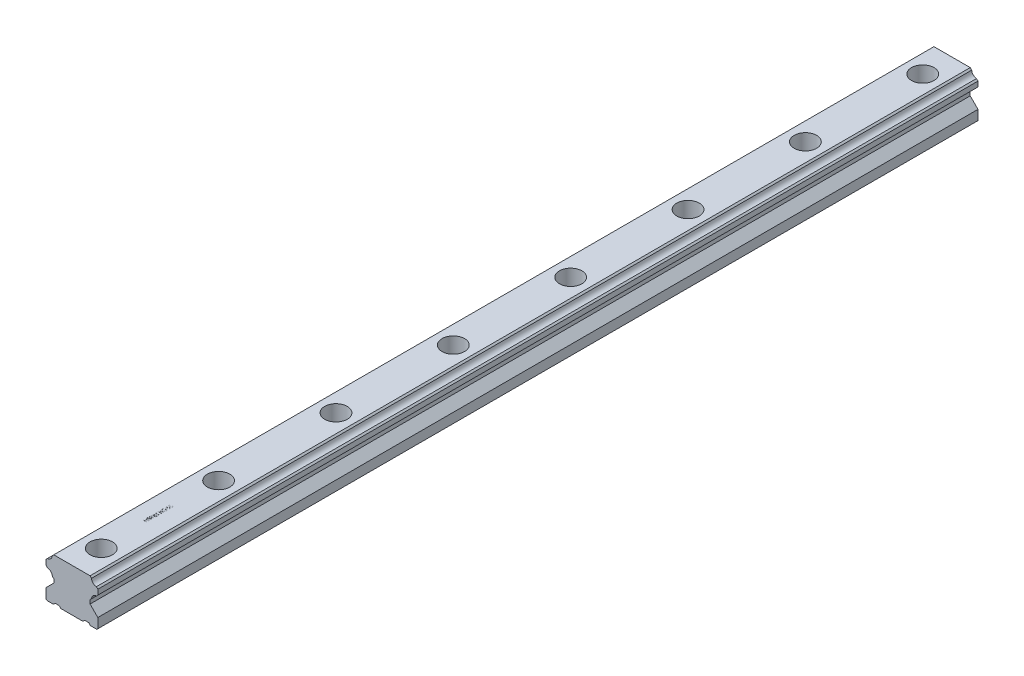
SolidWorks part; units mm, degrees
material "镀铬不锈钢"
ref_plane "前视基准面" through (0, 0, 0) normal (0, 0, 1) x (1, 0, 0)
ref_plane "上视基准面" through (0, 0, 0) normal (0, 1, 0) x (1, 0, 0)
ref_plane "右视基准面" through (0, 0, 0) normal (1, 0, 0) x (0, 0, -1)
sketch "草图1" plane through (0, 0, 0) normal (0, 0, 1) x (1, 0, 0)
  line L28 (26.5, 36.05) -> (25.0038, 37.5462)
  line L29 (-25.0038, 37.5462) -> (-26.5, 36.05)
  line L30 (-26.5, 30.8) -> (-25.0038, 29.3038)
  line L31 (-26.5, 36.05) -> (-26.5, 30.8)
  line L32 (-18.55, 44) -> (-20.0462, 42.5038)
  line L33 (13.1238, 1.7667) -> (17.1619, 1.7667)
  line L34 (-25.5, 0) -> (-18.9286, 0)
  line L35 (25.5, 0) -> (26.5, 1)
  line L36 (20.0462, 42.5038) -> (18.55, 44)
  line L37 (-26.5, 1) -> (-25.5, 0)
  line L38 (-20.0462, 24.3462) -> (-18.55, 22.85)
  line L39 (26.5, 11) -> (18.55, 18.95)
  line L40 (18.55, 44) -> (-18.55, 44)
  line L41 (-26.5, 11) -> (-26.5, 1)
  line L42 (17.1619, 1.7667) -> (18.9286, 0)
  line L43 (-18.55, 18.95) -> (-26.5, 11)
  line L44 (-17.1619, 1.7667) -> (-13.1238, 1.7667)
  line L45 (-13.1238, 1.7667) -> (-11.3571, 0)
  line L46 (-11.3571, 0) -> (11.3571, 0)
  line L47 (11.3571, 0) -> (13.1238, 1.7667)
  line L48 (26.5, 30.8) -> (26.5, 36.05)
  line L49 (-18.9286, 0) -> (-17.1619, 1.7667)
  line L50 (-18.55, 22.85) -> (-18.55, 18.95)
  line L51 (18.9286, 0) -> (25.5, 0)
  line L52 (18.55, 18.95) -> (18.55, 22.85)
  line L53 (18.55, 22.85) -> (20.0462, 24.3462)
  line L54 (26.5, 1) -> (26.5, 11)
  line L55 (25.0038, 29.3038) -> (26.5, 30.8)
  arc A4 (20.0462, 42.5038) -> (25.0038, 37.5462) centre (25.3357, 42.8357) ccw
  arc A5 (-20.0462, 24.3462) -> (-25.0038, 29.3038) centre (-25.3357, 24.0143) ccw
  arc A6 (25.0038, 29.3038) -> (20.0462, 24.3462) centre (25.3357, 24.0143) ccw
  arc A7 (-25.0038, 37.5462) -> (-20.0462, 42.5038) centre (-25.3357, 42.8357) ccw
extrude "凸台-拉伸1" add sketch "草图1" against normal blind 900
hole_wizard "打孔尺寸根据内六角圆柱头螺钉的类型1" positions "草图3" profile "草图2" counterbore size "M14" standard "GB" end condition through all
sketch "草图3" plane through (-6.516, 44, -115.069) normal (0, 1, 0) x (-1, 0, 0)
  point P0 (-6.516, 85.069)
  dimension "D1" = 30
sketch "草图2" plane through (0, 44, -30) normal (1, 0, 0) x (0, 0, 1)
  line L0 (0, 0) -> (0, 44)
  line L1 (0, 44) -> (8, 44)
  line L3 (8, 44) -> (8, 20)
  line L4 (8, 20) -> (11.5, 20)
  line L5 (11.5, 20) -> (11.5, 0)
  line L7 (11.5, 0) -> (0, 0)
  line L11 (0, -6.35) -> (0, 107.95) construction
  dimension "通孔孔直径" = 16
  dimension "通孔孔深度" = 44
  dimension "柱形沉头孔直径" = 23
  dimension "柱形沉头孔深度" = 20
pattern_linear "阵列(线性)1" count 8 spacing 120 along (0, 0, -1) of "打孔尺寸根据内六角圆柱头螺钉的类型1"
sketch "草图6" plane through (0, 44, 0) normal (0, 1, 0) x (1, 0, 0)
  line L0 (0, 30) -> (0, 150) construction
  text T0 "HIWIN HG55"
extrude "切除-拉伸1" cut sketch "草图6" against normal blind 0.1
equation "\"D1@凸台-拉伸1\" = 2 * \"D1@草图3\" + \"D3@阵列(线性)1\" *  ( \"D1@阵列(线性)1\"  - 1) "
